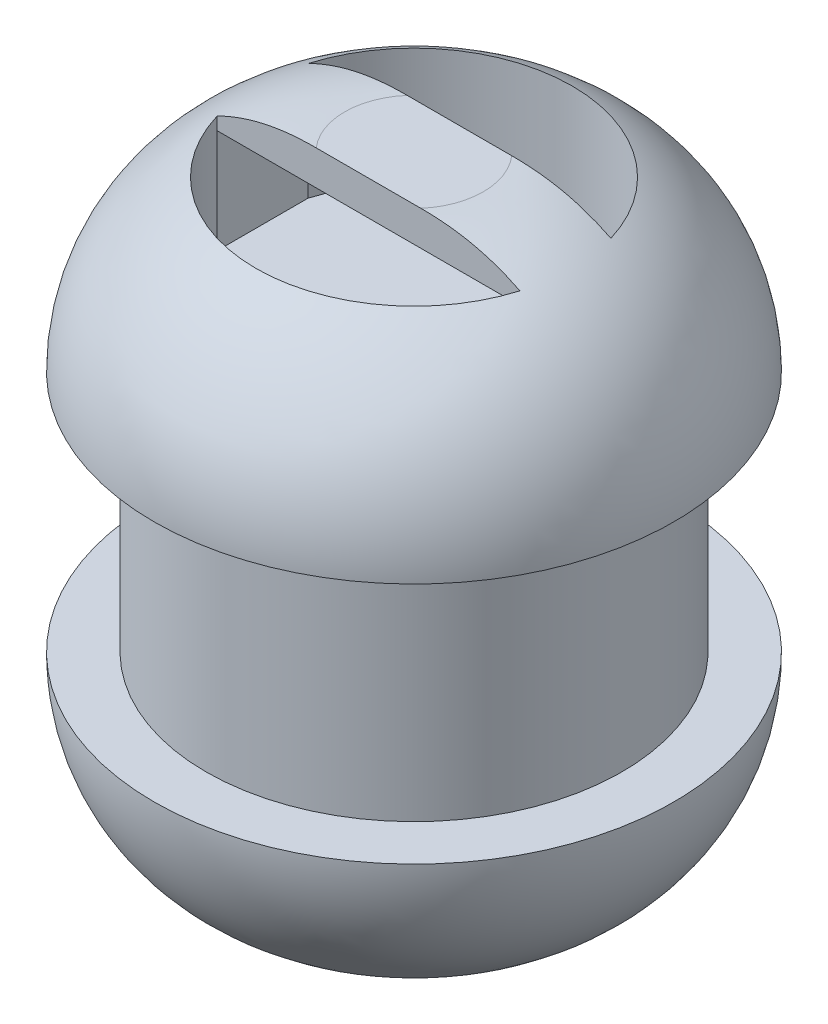
SolidWorks part; units mm, degrees
ref_plane "Front Plane" through (0, 0, 0) normal (0, 0, 1) x (1, 0, 0)
ref_plane "Top Plane" through (0, 0, 0) normal (0, 1, 0) x (1, 0, 0)
ref_plane "Right Plane" through (0, 0, 0) normal (1, 0, 0) x (0, 0, -1)
sketch "Sketch1" plane through (0, 0, 0) normal (0, 1, 0) x (1, 0, 0)
  circle A0 centre (0, 0) radius 30
  dimension "D1" = 60
extrude "Boss-Extrude1" add sketch "Sketch1" along normal mid plane 72
fillet "Fillet1" radius 22 1 edges at (0, 36, 30)
fillet "Fillet2" radius 22 1 edges at (0, -36, 30)
sketch "Sketch3" plane through (0, 0, 0) normal (0, 1, 0) x (1, 0, 0)
  circle A0 centre (0, 0) radius 24
  point P3 (0, 0)
  dimension "D1" = 48
extrude "Cut-Extrude2" cut sketch "Sketch3" against normal mid plane 28 flip side to cut
sketch "Sketch4" plane through (0, 36, 0) normal (0, 1, 0) x (1, 0, 0)
  line L5 (-17.4786, -5.25) -> (17.4786, -5.25)
  line L6 (-17.4786, -5.25) -> (-17.4786, 5.25) construction
  line L7 (-17.4786, 5.25) -> (17.4786, 5.25)
  line L8 (17.4786, -5.25) -> (17.4786, 5.25) construction
  line L9 (-17.4786, -5.25) -> (17.4786, 5.25) construction
  line L10 (-17.4786, 5.25) -> (17.4786, -5.25) construction
  circle A3 centre (0, 0) radius 18.25
  circle M7 centre (0, 0) radius 8
  dimension "D1" = 36.5
  dimension "D2" = 10.5
extrude "Cut-Extrude3" cut sketch "Sketch4" against normal blind 16 contours L7 M7 | L7 A3 M7 | L5 M7 | L5 A3 M7
ref_plane "Plane1" through (0, 32, 0) normal (0, 1, 0) x (1, 0, 0)
ref_plane "Plane2" through (0, 20, 0) normal (0, 1, 0) x (1, 0, 0)
sketch "Sketch6" plane through (0, 20, 0) normal (0, 1, 0) x (1, 0, 0)
  line L1 (-17.4786, -5.25) -> (17.4786, -5.25)
  line L2 (-17.4786, -5.25) -> (-17.4786, 5.25)
  line L3 (-17.4786, 5.25) -> (17.4786, 5.25)
  line L4 (17.4786, -5.25) -> (17.4786, 5.25)
  line L5 (-17.4786, -5.25) -> (17.4786, 5.25) construction
  line L6 (-17.4786, 5.25) -> (17.4786, -5.25) construction
  point P0 (0, 0)
extrude "Cut-Extrude9" cut sketch "Sketch6" along normal up to surface (12 mm away)
